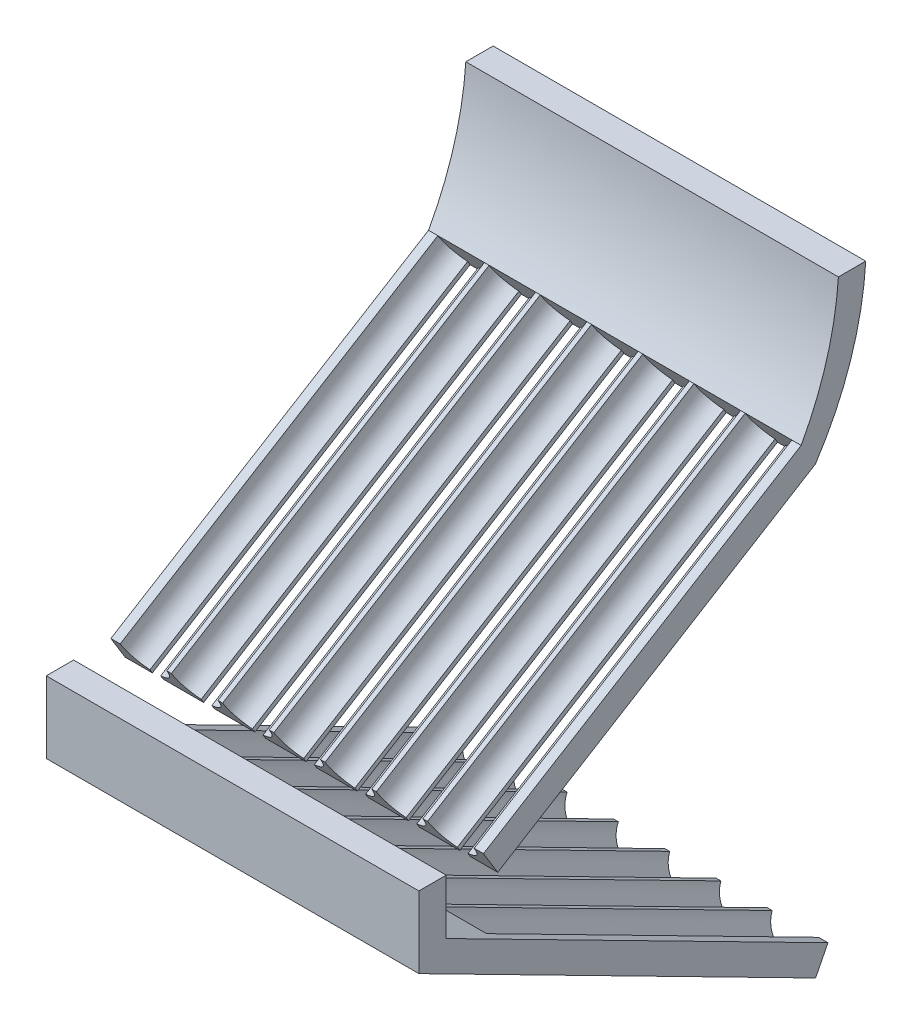
SolidWorks part; units mm, degrees
ref_plane "Front Plane" through (0, 0, 0) normal (0, 0, 1) x (1, 0, 0)
ref_plane "Top Plane" through (0, 0, 0) normal (0, 1, 0) x (1, 0, 0)
ref_plane "Right Plane" through (0, 0, 0) normal (1, 0, 0) x (0, 0, -1)
sketch "Sketch1" plane through (0, 0, 0) normal (1, 0, 0) x (0, 0, -1)
  line L0 (0, 0) -> (1023.1682, 626.9983)
  line L1 (0, 0) -> (-45.9799, 75.0323)
  line L2 (-45.9799, 75.0323) -> (977.1883, 702.0306)
  line L3 (977.1883, 702.0306) -> (1023.1682, 626.9983)
  line L4 (0, 0) -> (-836.2096, -512.4299) construction
  line L5 (-45.9799, 75.0323) -> (-1118.8823, 75.0323) construction
  line L6 (-165.9799, -101.7126) -> (-165.9799, 75.0323)
  line L7 (-165.9799, 75.0323) -> (-253.9799, 75.0323)
  line L8 (-253.9799, 75.0323) -> (-253.9799, -155.6391)
  line L9 (-165.9799, -101.7126) -> (1063.6091, -728.2195)
  line L10 (1063.6091, -728.2195) -> (732.4453, -1378.1651) construction
  line L11 (-253.9799, -155.6391) -> (1023.658, -806.6281)
  line L12 (1063.6091, -728.2195) -> (1023.658, -806.6281)
  line L13 (977.1883, 702.0306) -> (977.1883, 1112.0306) construction
  line L14 (977.1883, 1112.0306) -> (1097.1883, 1112.0306) construction
  line L16 (1097.1883, 1112.0306) -> (1185.1883, 1112.0306)
  arc A0 (1097.1883, 1112.0306) -> (977.1883, 702.0306) centre (111.833, 1177.8663) cw
  arc A1 (1023.1682, 626.9983) -> (1185.1883, 1112.0306) centre (199.4423, 1171.7323) ccw
  dimension "D1" = 1200
  dimension "D2" = 88
  dimension "D3" = 120
  dimension "D4" = 88
  dimension "D5" = 1380
  dimension "D6" = 90
  dimension "D7" = 88
  dimension "D8" = 410
  dimension "D9" = 120
  dimension "D10" = 88
extrude "Boss-Extrude1" add sketch "Sketch1" along normal blind 1200 contours L3 A1 L16 A0 | L3 L2 L1 L0 | L12 L9 L6 L7 L8 L11
ref_plane "Plane1" through (0, 0, 0) normal (0, -0.5225, 0.8526) x (1, 0, 0)
sketch "Sketch3" plane through (0, 0, 0) normal (0, -0.5225, 0.8526) x (1, 0, 0)
  line L5 (525, 88) -> (675, 88)
  line L6 (582.7953, 15) -> (582.7953, 0)
  line L7 (1200, 0) -> (0, 0) construction
  line L8 (617.2047, 15) -> (617.2047, 0)
  line L9 (582.7953, 0) -> (617.2047, 0)
  line L10 (682.5, 88) -> (682.5, 0) construction
  line L11 (1200, 88) -> (0, 88) construction
  line L12 (747.7953, 15) -> (747.7953, 0)
  line L13 (782.2047, 0) -> (747.7953, 0)
  line L14 (782.2047, 15) -> (782.2047, 0)
  line L15 (840, 88) -> (690, 88)
  line L16 (847.5, 88) -> (847.5, 0) construction
  line L17 (1077.7953, 15) -> (1077.7953, 0)
  line L18 (1112.2047, 0) -> (1077.7953, 0)
  line L19 (1112.2047, 15) -> (1112.2047, 0)
  line L20 (1170, 88) -> (1020, 88)
  line L21 (855, 88) -> (1005, 88)
  line L22 (912.7953, 15) -> (912.7953, 0)
  line L23 (912.7953, 0) -> (947.2047, 0)
  line L24 (947.2047, 15) -> (947.2047, 0)
  line L25 (30, 88) -> (180, 88)
  line L26 (87.7953, 15) -> (87.7953, 0)
  line L27 (87.7953, 0) -> (122.2047, 0)
  line L28 (122.2047, 15) -> (122.2047, 0)
  line L29 (252.7953, 15) -> (252.7953, 0)
  line L30 (287.2047, 0) -> (252.7953, 0)
  line L31 (287.2047, 15) -> (287.2047, 0)
  line L32 (345, 88) -> (195, 88)
  line L33 (360, 88) -> (510, 88)
  line L34 (417.7953, 15) -> (417.7953, 0)
  line L35 (417.7953, 0) -> (452.2047, 0)
  line L36 (452.2047, 15) -> (452.2047, 0)
  line L37 (582.7953, 15) -> (582.7953, 0)
  line L38 (617.2047, 15) -> (617.2047, 0)
  arc A0 (525, 88) -> (582.7953, 15) centre (600, 88) ccw
  arc A1 (617.2047, 15) -> (675, 88) centre (600, 88) ccw
  arc A2 (840, 88) -> (782.2047, 15) centre (765, 88) cw
  arc A3 (747.7953, 15) -> (690, 88) centre (765, 88) cw
  arc A4 (1170, 88) -> (1112.2047, 15) centre (1095, 88) cw
  arc A5 (1077.7953, 15) -> (1020, 88) centre (1095, 88) cw
  arc A6 (947.2047, 15) -> (1005, 88) centre (930, 88) ccw
  arc A7 (855, 88) -> (912.7953, 15) centre (930, 88) ccw
  arc A8 (122.2047, 15) -> (180, 88) centre (105, 88) ccw
  arc A9 (30, 88) -> (87.7953, 15) centre (105, 88) ccw
  arc A10 (345, 88) -> (287.2047, 15) centre (270, 88) cw
  arc A11 (252.7953, 15) -> (195, 88) centre (270, 88) cw
  arc A12 (452.2047, 15) -> (510, 88) centre (435, 88) ccw
  arc A13 (360, 88) -> (417.7953, 15) centre (435, 88) ccw
  arc A14 (675, 88) -> (617.2047, 15) centre (600, 88) cw
  arc A15 (582.7953, 15) -> (525, 88) centre (600, 88) cw
  dimension "D2" = 150
  dimension "D3" = 15
  dimension "D4" = 7.5
  dimension "D5" = 7.5
extrude "Cut-Extrude1" cut sketch "Sketch3" against normal blind 1200 contours L25 A9 L26 L27 L28 A8 | A11 L29 L30 L31 A10 L32 | L33 A13 L34 L35 L36 A12 | L8 A1 L5 A0 L6 L9 | A3 L12 L13 L14 A2 L15 | L21 A7 L22 L23 L24 A6 | A5 L17 L18 L19 A4 L20
sketch "Sketch4" plane through (0, -580.3303, -1138.9624) normal (0, -0.454, -0.891) x (-1, 0, 0)
  line L1 (-1200, -165.9799) -> (0, -165.9799) construction
  line L2 (-675, -165.9799) -> (-525, -165.9799)
  line L3 (-617.2047, -238.9799) -> (-617.2047, -253.9799)
  line L4 (-1200, -253.9799) -> (0, -253.9799) construction
  line L5 (-581.3387, -238.6212) -> (-582.7953, -253.9799)
  line L6 (-617.2047, -253.9799) -> (-582.7953, -253.9799)
  line L7 (-517.5, -165.9799) -> (-517.5, -266.8118) construction
  line L8 (-453.6613, -238.6212) -> (-452.2047, -253.9799)
  line L9 (-417.7953, -253.9799) -> (-452.2047, -253.9799)
  line L10 (-417.7953, -238.9799) -> (-417.7953, -253.9799)
  line L11 (-360, -165.9799) -> (-510, -165.9799)
  line L12 (-352.5, -165.9799) -> (-352.5, -261.4119) construction
  line L13 (-345, -165.9799) -> (-195, -165.9799)
  line L14 (-287.2047, -238.9799) -> (-287.2047, -253.9799)
  line L15 (-287.2047, -253.9799) -> (-252.7953, -253.9799)
  line L16 (-251.3387, -238.6212) -> (-252.7953, -253.9799)
  line L17 (-123.6613, -238.6212) -> (-122.2047, -253.9799)
  line L18 (-87.7953, -253.9799) -> (-122.2047, -253.9799)
  line L19 (-87.7953, -238.9799) -> (-87.7953, -253.9799)
  line L20 (-30, -165.9799) -> (-180, -165.9799)
  line L21 (-1170, -159.9512) -> (-1020, -159.9512)
  line L22 (-1112.2047, -232.9512) -> (-1112.2047, -247.9512)
  line L23 (-1112.2047, -247.9512) -> (-1077.7953, -247.9512)
  line L24 (-1077.7953, -232.9512) -> (-1077.7953, -247.9512)
  line L25 (-947.2047, -232.9512) -> (-947.2047, -247.9512)
  line L26 (-912.7953, -247.9512) -> (-947.2047, -247.9512)
  line L27 (-912.7953, -232.9512) -> (-912.7953, -247.9512)
  line L28 (-855, -159.9512) -> (-1005, -159.9512)
  line L29 (-840, -159.9512) -> (-690, -159.9512)
  line L30 (-782.2047, -232.9512) -> (-782.2047, -247.9512)
  line L31 (-782.2047, -247.9512) -> (-747.7953, -247.9512)
  line L32 (-747.7953, -232.9512) -> (-747.7953, -247.9512)
  line L33 (-617.2047, -238.9799) -> (-617.2047, -253.9799)
  line L34 (-581.3387, -238.6212) -> (-582.7953, -253.9799)
  arc A0 (-675, -165.9799) -> (-617.2047, -238.9799) centre (-600, -165.9799) ccw
  arc A1 (-581.3387, -238.6212) -> (-525, -165.9799) centre (-600, -165.9799) ccw
  arc A2 (-360, -165.9799) -> (-417.7953, -238.9799) centre (-435, -165.9799) cw
  arc A3 (-453.6613, -238.6212) -> (-510, -165.9799) centre (-435, -165.9799) cw
  arc A4 (-251.3387, -238.6212) -> (-195, -165.9799) centre (-270, -165.9799) ccw
  arc A5 (-345, -165.9799) -> (-287.2047, -238.9799) centre (-270, -165.9799) ccw
  arc A6 (-30, -165.9799) -> (-87.7953, -238.9799) centre (-105, -165.9799) cw
  arc A7 (-123.6613, -238.6212) -> (-180, -165.9799) centre (-105, -165.9799) cw
  arc A8 (-1077.7953, -232.9512) -> (-1020, -159.9512) centre (-1095, -159.9512) ccw
  arc A9 (-1170, -159.9512) -> (-1112.2047, -232.9512) centre (-1095, -159.9512) ccw
  arc A10 (-855, -159.9512) -> (-912.7953, -232.9512) centre (-930, -159.9512) cw
  arc A11 (-947.2047, -232.9512) -> (-1005, -159.9512) centre (-930, -159.9512) cw
  arc A12 (-747.7953, -232.9512) -> (-690, -159.9512) centre (-765, -159.9512) ccw
  arc A13 (-840, -159.9512) -> (-782.2047, -232.9512) centre (-765, -159.9512) ccw
  arc A14 (-525, -165.9799) -> (-581.3387, -238.6212) centre (-600, -165.9799) cw
  arc A15 (-617.2047, -238.9799) -> (-675, -165.9799) centre (-600, -165.9799) cw
  line M6 (0, -165.9799) -> (-1200, -165.9799)
  line M8 (-1200, -253.9799) -> (0, -253.9799)
  dimension "D1" = 150
  dimension "D2" = 15
  dimension "D3" = 7.5
  dimension "D4" = 7.5
extrude "Cut-Extrude2" cut sketch "Sketch4" against normal blind 1200 contours A9 L22 L24 A8 M6 M8 | A11 L25 L27 A10 M8 M6 | A13 L30 L32 A12 M6 M8 | L5 A1 A0 L3 M6 M8 | A3 L8 L10 A2 M8 M6 | A5 L14 L16 A4 M6 M8 | A7 L17 L19 A6 M8 M6
